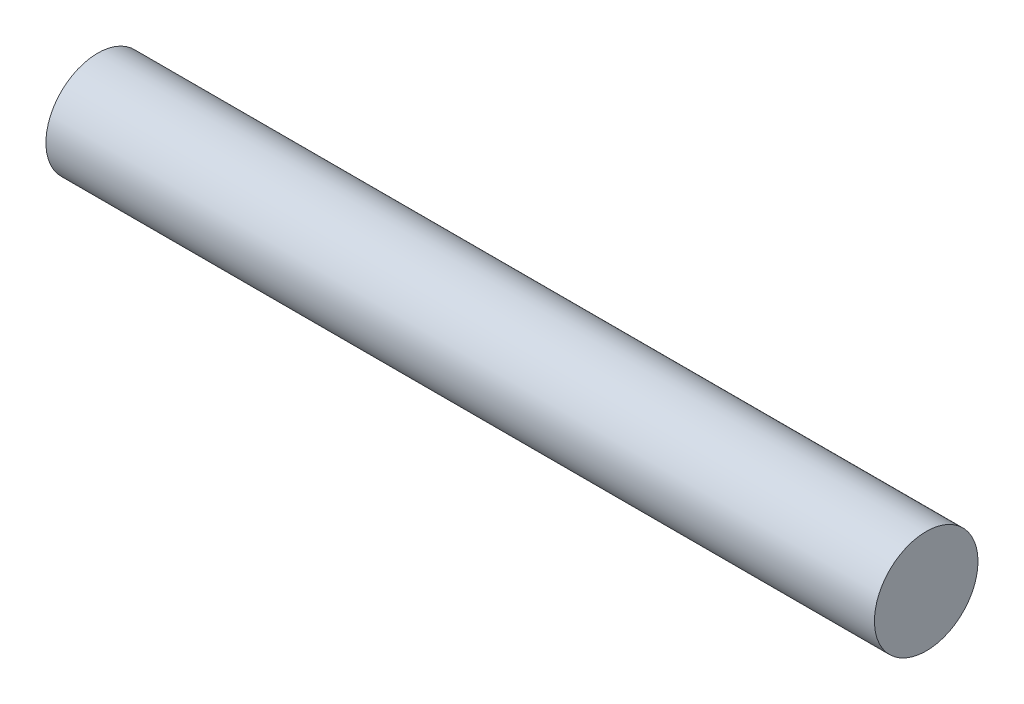
SolidWorks part; units mm, degrees
ref_plane "Alzado" through (0, 0, 0) normal (0, 0, 1) x (1, 0, 0)
ref_plane "Planta" through (0, 0, 0) normal (0, 1, 0) x (1, 0, 0)
ref_plane "Vista lateral" through (0, 0, 0) normal (1, 0, 0) x (0, 0, -1)
sketch "Croquis1" plane through (0, 0, 0) normal (1, 0, 0) x (0, 0, -1)
  circle A0 centre (0, 0) radius 1
  dimension "D1" = 2
extrude "Saliente-Extruir1" add sketch "Croquis1" along normal mid plane 16
